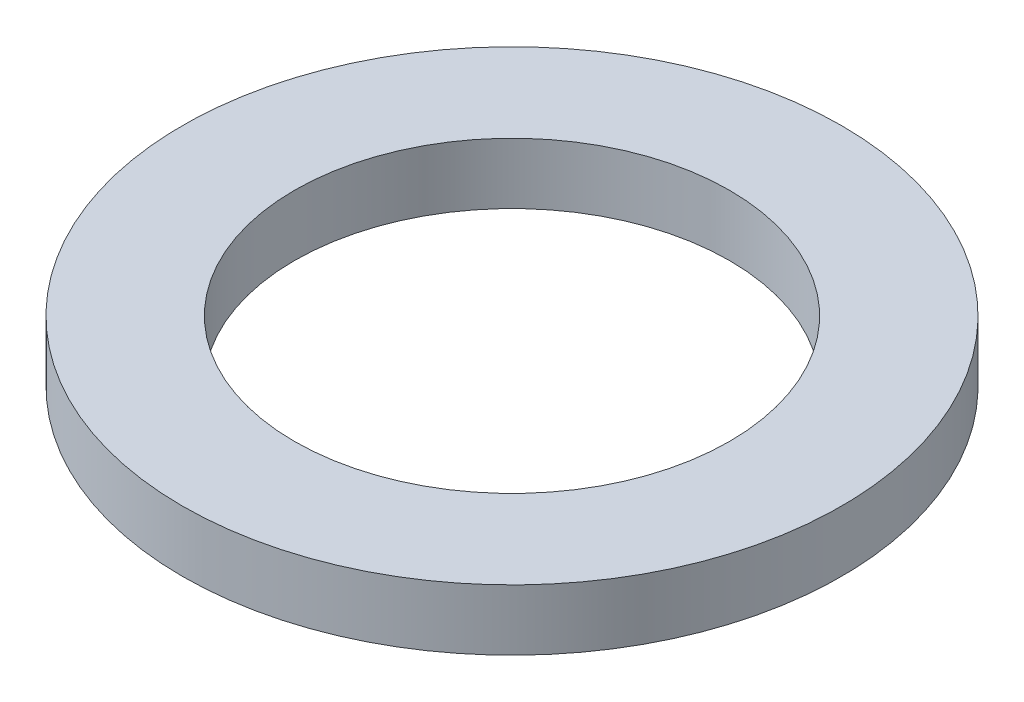
SolidWorks part; units mm, degrees
ref_plane "Front Plane" through (0, 0, 0) normal (0, 0, 1) x (1, 0, 0)
ref_plane "Top Plane" through (0, 0, 0) normal (0, 1, 0) x (1, 0, 0)
ref_plane "Right Plane" through (0, 0, 0) normal (1, 0, 0) x (0, 0, -1)
sketch "Sketch1" plane through (0, 0, 0) normal (0, 1, 0) x (1, 0, 0)
  circle A0 centre (0, 0) radius 3.8481
  dimension "OD" = 7.6962
extrude "Boss-Extrude1" add sketch "Sketch1" along normal blind 0.7112
sketch "Sketch5" plane through (0, 0.7112, 0) normal (0, 1, 0) x (-1, 0, 0)
  circle A0 centre (0, 0) radius 2.54
  dimension "ID" = 5.08
extrude "Cut-Extrude1" cut sketch "Sketch5" against normal through all
